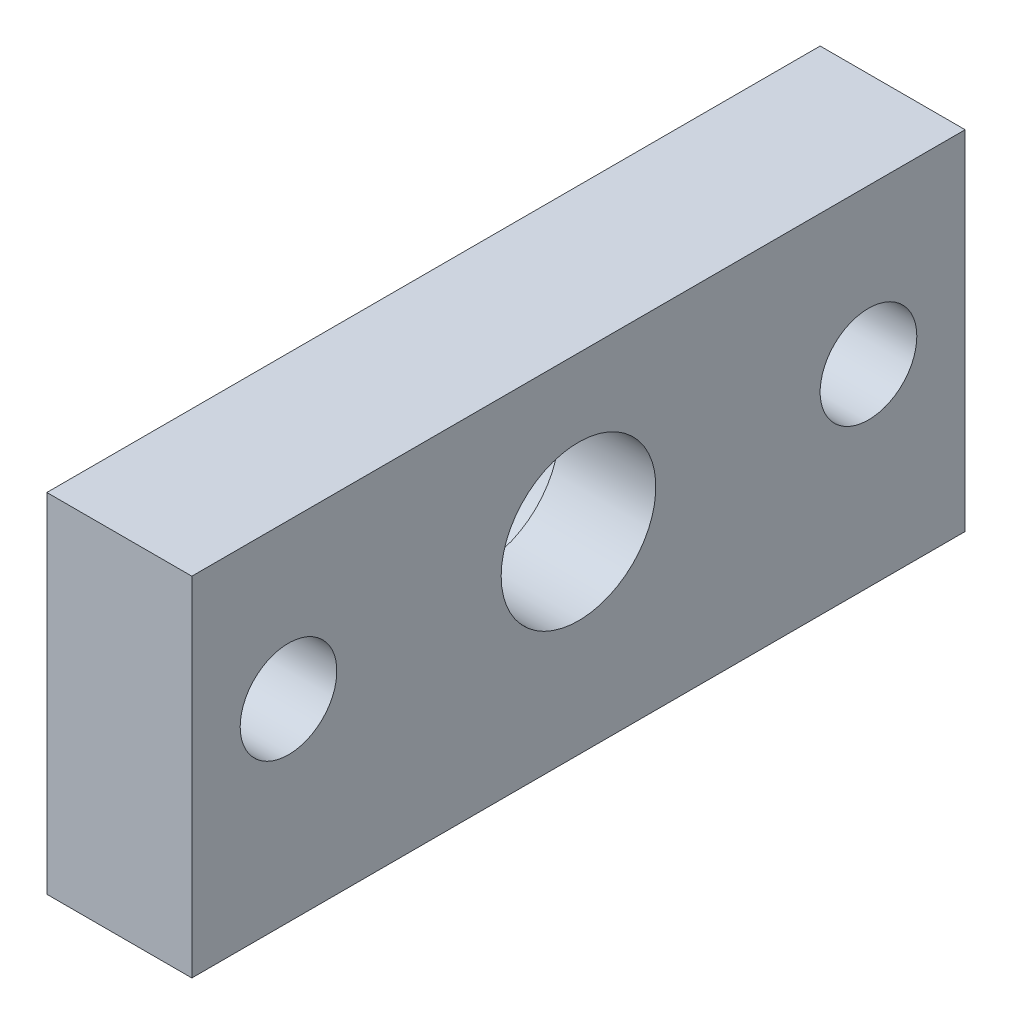
SolidWorks part; units mm, degrees
ref_plane "前视基准面" through (0, 0, 0) normal (0, 0, 1) x (1, 0, 0)
ref_plane "上视基准面" through (0, 0, 0) normal (0, 1, 0) x (1, 0, 0)
ref_plane "右视基准面" through (0, 0, 0) normal (1, 0, 0) x (0, 0, -1)
sketch "草图1" plane through (0, 0, 0) normal (1, 0, 0) x (0, 0, -1)
  line L1 (-40, -18) -> (40, -18)
  line L2 (-40, -18) -> (-40, 18)
  line L3 (-40, 18) -> (40, 18)
  line L4 (40, -18) -> (40, 18)
  line L5 (-40, -18) -> (40, 18) construction
  line L6 (-40, 18) -> (40, -18) construction
  point P0 (0, 0)
  dimension "D1" = 36
  dimension "D2" = 80
extrude "凸台-拉伸1" add sketch "草图1" along normal blind 15
sketch "草图2" plane through (0, -18, 0) normal (0, -1, 0) x (1, 0, 0)
  line L0 (7.5, 40) -> (7.5, -40) construction
  line L1 (15, 40) -> (0, 40) construction
  line L2 (15, -40) -> (0, -40) construction
  point P0 (7.5, 30)
  point P9 (7.5, 10)
  point P10 (7.5, -10)
  point P11 (7.5, -30)
  dimension "D1" = 10
  dimension "D3" = 20
  dimension "D2" = 4
hole_wizard "M6 螺纹孔1" positions "草图2" profile "草图3" tap size "M6" standard "GB"
sketch "草图3" plane through (7.5, -18, 30) normal (1, 0, 0) x (0, 0, -1)
  line L0 (0, 0) -> (0, 9.5022)
  line L1 (0, 9.5022) -> (2.5, 8)
  line L2 (2.5, 8) -> (2.5, 0)
  line L5 (2.5, 0) -> (0, 0)
  line L10 (0, 9.5022) -> (-2.5, 8) construction
  line L11 (0, -6.35) -> (0, 107.95) construction
  dimension "螺纹孔钻头直径" = 5
  dimension "螺纹孔钻头深度" = 8
  dimension "导头角度" = 118
cosmetic thread "孔螺纹线1" parameters "D1"=6, "D2"=6
cosmetic thread "孔螺纹线2" parameters "D1"=6, "D2"=6
cosmetic thread "孔螺纹线3" parameters "D1"=6, "D2"=6
cosmetic thread "孔螺纹线4" parameters "D1"=6, "D2"=6
ref_plane "基准面1" through (0, -38, 0) normal (0, 1, 0) x (1, 0, 0)
sketch "草图4" plane through (0, 0, 0) normal (-1, 0, 0) x (0, 0, 1)
  circle A0 centre (0, 2) radius 12
  dimension "D1" = 24
  dimension "D2" = 2
extrude "切除-拉伸1" cut sketch "草图4" against normal blind 5
sketch "草图5" plane through (0, 0, 0) normal (-1, 0, 0) x (0, 0, 1)
  line L0 (40, 18) -> (40, -18) construction
  circle A0 centre (30, 2) radius 5
  dimension "D1" = 10
  dimension "D2" = 10
  dimension "D3" = 2
extrude "切除-拉伸2" cut sketch "草图5" against normal blind 15
mirror "镜向1" about plane through (0, 0, 0) normal (0, 0, 1) of "切除-拉伸2"
sketch "草图6" plane through (5, 0, 0) normal (-1, 0, 0) x (0, 0, 1)
  circle A0 centre (0, 2) radius 8
  circle A1 centre (0, 2) radius 12 construction
  dimension "D1" = 16
extrude "切除-拉伸3" cut sketch "草图6" against normal through all
